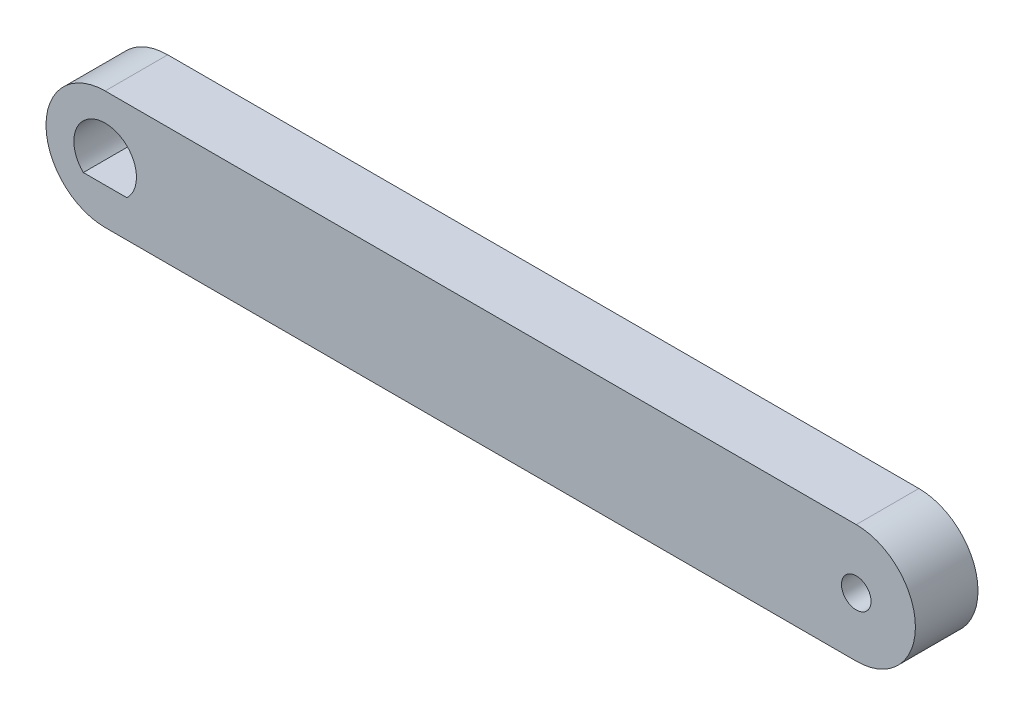
SolidWorks part; units mm, degrees
ref_plane "Plan de face" through (0, 0, 0) normal (0, 0, 1) x (1, 0, 0)
ref_plane "Plan de dessus" through (0, 0, 0) normal (0, 1, 0) x (1, 0, 0)
ref_plane "Plan de droite" through (0, 0, 0) normal (1, 0, 0) x (0, 0, -1)
sketch "Esquisse1" plane through (0, 0, 0) normal (0, 0, 1) x (1, 0, 0)
  line L0 (0, 0) -> (76.2, 0) construction
  line L1 (0, 6) -> (76.2, 6)
  line L2 (0, -6) -> (76.2, -6)
  arc A0 (0, 6) -> (0, -6) centre (0, 0) ccw
  arc A1 (76.2, -6) -> (76.2, 6) centre (76.2, 0) ccw
  point P3 (38.1, 0)
  dimension "D2" = 6
  dimension "D1" = 76.2
extrude "Boss.-Extru.1" add sketch "Esquisse1" along normal blind 6.35
sketch "Esquisse2" plane through (0, 0, 6.35) normal (0, 0, 1) x (1, 0, 0)
  line L0 (-2.2147, -2.275) -> (2.2147, -2.275)
  arc A0 (2.2147, -2.275) -> (-2.2147, -2.275) centre (0, 0) ccw
  dimension "D1" = 6.35
  dimension "D2" = 2.275
extrude "Enlèv. mat.-Extru.1" cut sketch "Esquisse2" against normal up to next
sketch "Esquisse3" plane through (0, 0, 6.35) normal (0, 0, 1) x (1, 0, 0)
  circle A0 centre (76.2, 0) radius 1.5
  dimension "D1" = 3
extrude "Enlèv. mat.-Extru.2" cut sketch "Esquisse3" against normal blind 6.35
